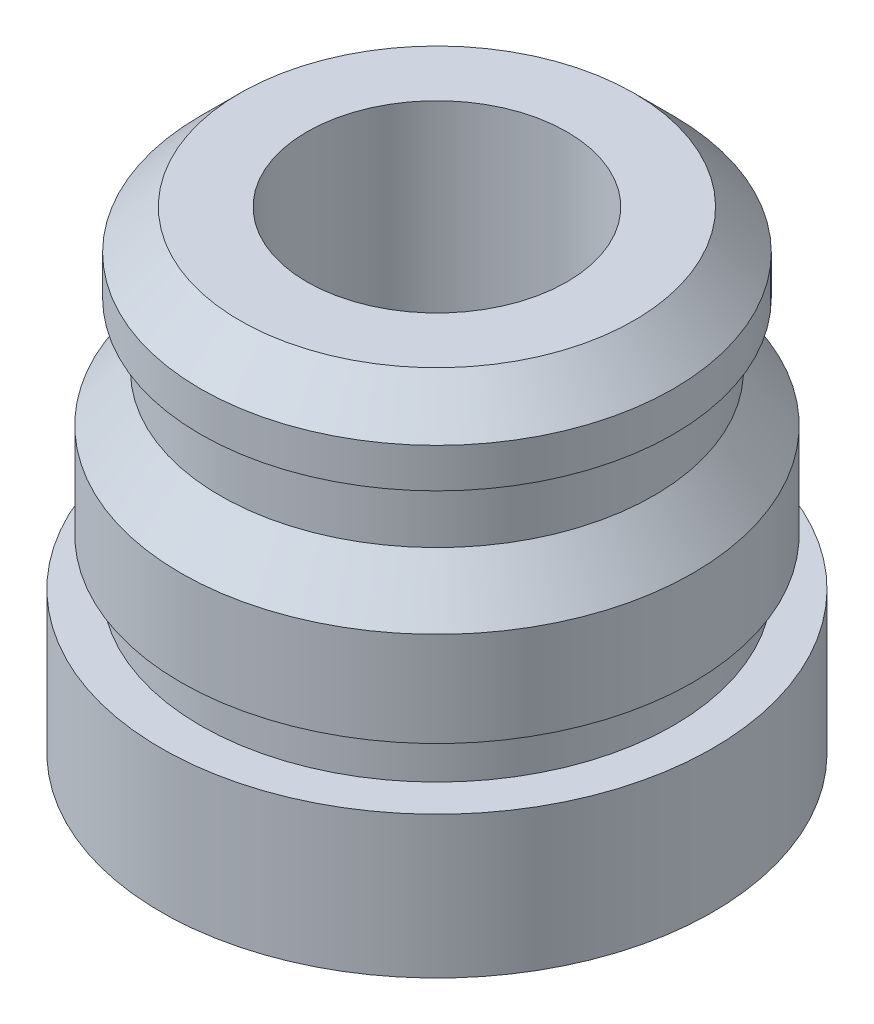
SolidWorks part; units mm, degrees
ref_plane "Спереди" through (0, 0, 0) normal (0, 0, 1) x (1, 0, 0)
ref_plane "Сверху" through (0, 0, 0) normal (0, 1, 0) x (1, 0, 0)
ref_plane "Справа" through (0, 0, 0) normal (1, 0, 0) x (0, 0, -1)
sketch "Эскиз2" plane through (0, 0, 0) normal (0, 0, 1) x (1, 0, 0)
  line L0 (0, 0) -> (0, 4.529) construction
  line L1 (1.5, -0.1221) -> (3.5, -0.1221)
  line L2 (3.5, -0.1221) -> (3.5, 1.6779)
  line L3 (3.5, 1.6779) -> (3, 1.6779)
  line L4 (3, 1.6779) -> (3, 2.2779)
  line L5 (3, 2.2779) -> (3.25, 2.2779)
  line L6 (3.25, 2.2779) -> (3.25, 3.4779)
  line L7 (3.25, 3.4779) -> (2.75, 4.0779)
  line L8 (2.75, 4.0779) -> (2.75, 4.8779)
  line L9 (2.75, 4.8779) -> (3, 4.8779)
  line L10 (3, 4.8779) -> (3, 5.3779)
  line L11 (3, 5.3779) -> (2.5, 5.8779)
  line L12 (2.5, 5.8779) -> (1.5, 5.8779)
  line L14 (1.5, 5.8779) -> (1.5, -0.1221)
  dimension "D1" = 6
  dimension "D2" = 7
  dimension "D3" = 135
  dimension "D4" = 3
  dimension "D5" = 6.5
  dimension "D6" = 6
  dimension "D7" = 5.5
  dimension "D8" = 6
  dimension "D9" = 1.8
  dimension "D10" = 0.6
  dimension "D11" = 1.2
  dimension "D12" = 0.5
  dimension "D13" = 0.5
  dimension "D14" = 0.8
revolve "Повернуть1" add sketch "Эскиз2" angle 360 about L0
hole_wizard "Отверстие обработанное метчиком M41" positions "Эскиз4" profile "Эскиз5" tap size "M4" standard "DIN" end condition through all
sketch "Эскиз4" plane through (0, -0.1221, 0) normal (0, -1, 0) x (-1, 0, 0)
  point P0 (0, 0)
sketch "Эскиз5" plane through (0, -0.1221, 0) normal (1, 0, 0) x (0, 0, -1)
  line L0 (0, 0) -> (0, 6)
  line L1 (0, 6) -> (1.65, 6)
  line L2 (1.65, 6) -> (1.65, 0)
  line L5 (1.65, 0) -> (0, 0)
  line L11 (0, -6.35) -> (0, 107.95) construction
  dimension "Диаметр проходного сверла" = 3.3
  dimension "Глубина проходного сверла" = 6
cosmetic thread "Отверстие резьбы1" parameters "D2"=4
